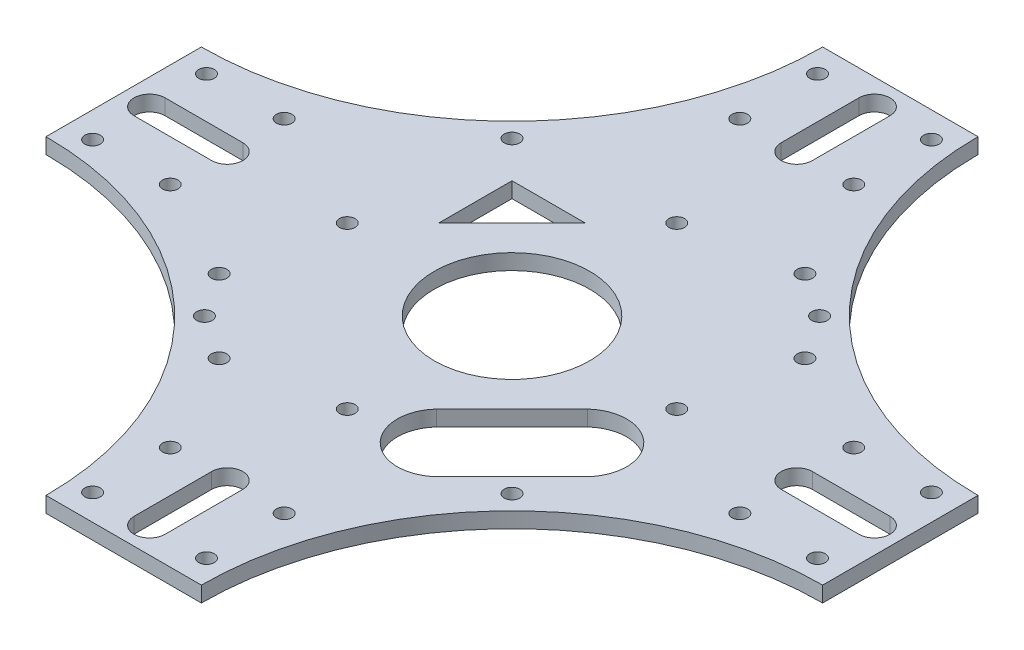
SolidWorks part; units mm, degrees
ref_plane "前视基准面" through (0, 0, 0) normal (0, 0, 1) x (1, 0, 0)
ref_plane "上视基准面" through (0, 0, 0) normal (0, 1, 0) x (1, 0, 0)
ref_plane "右视基准面" through (0, 0, 0) normal (1, 0, 0) x (0, 0, -1)
sketch "草图1" plane through (0, 0, 0) normal (0, 1, 0) x (1, 0, 0)
  line L0 (0, 0) -> (0, 75)
  line L1 (0, 0) -> (75, 0)
  line L2 (0, 0) -> (0, -75)
  line L3 (0, 0) -> (-75, 0)
  line L4 (0, 75) -> (15, 75)
  line L5 (0, 75) -> (-15, 75)
  line L6 (75, 0) -> (75, 15)
  line L7 (75, 0) -> (75, -15)
  line L8 (0, -75) -> (15, -75)
  line L9 (0, -75) -> (-15, -75)
  line L10 (-75, 0) -> (-75, -15)
  line L11 (-75, 0) -> (-75, 15)
  line L12 (75, 0) -> (70, 0)
  arc A0 (-75, 15) -> (-15, 75) centre (-75, 75) ccw
  arc A1 (15, 75) -> (75, 15) centre (75, 75) ccw
  arc A2 (75, -15) -> (15, -75) centre (75, -75) ccw
  arc A3 (-15, -75) -> (-75, -15) centre (-75, -75) ccw
  circle A4 centre (-11, 70) radius 1.25
  circle A5 centre (11, 70) radius 1.25
  circle A6 centre (70, -11) radius 1.25
  circle A7 centre (70, 11) radius 1.25
  circle A8 centre (-11, -70) radius 1.25
  circle A9 centre (11, -70) radius 1.25
  circle A10 centre (-70, 11) radius 1.25
  circle A11 centre (-70, -11) radius 1.25
  point P9 (0, 0)
  point P21 (0, 0)
  point P32 (0, 0)
  point P35 (0, 0)
  point P44 (0, 0)
  dimension "D1" = 4
extrude "凸台-拉伸1" add sketch "草图1" along normal blind 3 contours A2 L7 L1 L2 L8 A9 A6 | A3 L9 L2 L3 L10 A11 A8 | A0 L11 L3 L0 L5 A4 A10 | A1 L4 L0 L1 L6 A7 A5
sketch "草图2" plane through (0, 0, 0) normal (0, -1, 0) x (1, 0, 0)
  line L0 (0, 0) -> (-32.5736, -32.5736)
  line L1 (0, 0) -> (32.5736, -32.5736)
  line L2 (-31.4663, 0.3536) -> (-0.3536, 31.4663)
  line L3 (31.4663, -0.3536) -> (-0.3536, 31.4663)
  line L4 (0.3536, -31.4663) -> (31.4663, -0.3536)
  line L5 (0.3536, -31.4663) -> (-31.4663, 0.3536)
  arc A0 (-15, -75) -> (-75, -15) centre (-75, -75) ccw construction
  circle A2 centre (0.3536, -31.4663) radius 1.5
  circle A3 centre (31.4663, -0.3536) radius 1.5
  circle A4 centre (-0.3536, 31.4663) radius 1.5
  circle A5 centre (-31.4663, 0.3536) radius 1.5
  point P12 (-15.5563, -15.5563)
  point P16 (-15.9099, 15.9099)
  point P17 (15.9099, -15.9099)
extrude "切除-拉伸1" cut sketch "草图2" against normal blind 3 contours A3 | A2 | A5 | A4
sketch "草图3" plane through (0, 3, 0) normal (0, 1, 0) x (1, 0, 0)
  line L0 (0.3536, 31.4663) -> (-31.4663, -0.3536)
  line L1 (-15.5563, 15.5563) -> (-22.6274, 22.6274)
  line L2 (-15.5563, 15.5563) -> (-12.0208, 19.0919)
  line L3 (-15.5563, 15.5563) -> (-19.0919, 12.0208)
  line L4 (-19.0919, 12.0208) -> (-22.6274, 22.6274)
  line L5 (-12.0208, 19.0919) -> (-22.6274, 22.6274)
extrude "切除-拉伸2" cut sketch "草图3" against normal blind 3 contours L0 L5 L1 | L4 L0 L1
sketch "草图4" plane through (0, 3, 0) normal (0, 1, 0) x (1, 0, 0)
  line L0 (31.4663, 0.3536) -> (-0.3536, -31.4663)
  line L1 (0, 0) -> (21.2132, -21.2132)
  line L2 (28.2843, -14.1421) -> (14.1421, -28.2843)
  line L3 (14.1421, -28.2843) -> (28.2843, -14.1421) construction
  line L4 (8.4817, -22.6239) -> (22.6239, -8.4817)
  line L5 (19.8025, -33.9447) -> (33.9447, -19.8025)
  arc A0 (8.4817, -22.6239) -> (19.8025, -33.9447) centre (14.1421, -28.2843) ccw
  arc A1 (33.9447, -19.8025) -> (22.6239, -8.4817) centre (28.2843, -14.1421) ccw
  point P9 (21.2132, -21.2132)
extrude "切除-拉伸3" cut sketch "草图4" against normal blind 3
sketch "草图5" plane through (0, 3, 0) normal (0, 1, 0) x (1, 0, 0)
  line L0 (-12.0208, 19.0919) -> (-8.4853, 22.6274)
  line L1 (-8.4853, 22.6274) -> (-22.6274, 22.6274)
  line L2 (-19.0919, 12.0208) -> (-22.6274, 8.4853)
  line L3 (-22.6274, 8.4853) -> (-22.6274, 22.6274)
  line L4 (-12.0208, 19.0919) -> (-22.6274, 22.6274)
  line M28 (-19.0919, 12.0208) -> (-22.6274, 22.6274)
extrude "切除-拉伸4" cut sketch "草图5" against normal blind 10 contours L3 L2 M28 | L4 L0 L1
sketch "草图6" plane through (0, 3, 0) normal (0, 1, 0) x (1, 0, 0)
  line L0 (0, 0) -> (-28.2843, -28.2843)
  line L1 (-28.2843, -28.2843) -> (-35.3553, -21.2132)
  line L2 (0, 0) -> (-22.6274, 22.6274)
  circle A0 centre (-35.3553, -21.2132) radius 1.5
  circle A1 centre (-21.2132, -35.3553) radius 1.5
  circle A2 centre (35.3553, 21.2132) radius 1.5
  circle A3 centre (21.2132, 35.3553) radius 1.5
extrude "切除-拉伸5" cut sketch "草图6" against normal blind 10 contours A1 | A0 | A2 | A3
sketch "草图7" plane through (0, 3, 0) normal (0, 1, 0) x (1, 0, 0)
  circle A0 centre (-29.6985, 29.6985) radius 1.5
  circle A1 centre (29.6985, 29.6985) radius 1.5
  circle A2 centre (29.6985, -29.6985) radius 1.5
  circle A3 centre (-29.6985, -29.6985) radius 1.5
  point P11 (0, 0)
  dimension "D1" = 4
extrude "切除-拉伸8" cut sketch "草图7" against normal blind 10
sketch "草图8" plane through (0, 3, 0) normal (0, 1, 0) x (1, 0, 0)
  circle A0 centre (-11, 55) radius 1.5
  circle A1 centre (11, 55) radius 1.5
  circle A2 centre (55, 11) radius 1.5
  circle A3 centre (55, -11) radius 1.5
  circle A4 centre (11, -55) radius 1.5
  circle A5 centre (-11, -55) radius 1.5
  circle A6 centre (-55, -11) radius 1.5
  circle A7 centre (-55, 11) radius 1.5
  point P21 (0, 0)
  dimension "D1" = 4
extrude "切除-拉伸9" cut sketch "草图8" against normal blind 10
sketch "草图9" plane through (0, 3, 0) normal (0, 1, 0) x (1, 0, 0)
  circle A0 centre (0, 0) radius 15
extrude "切除-拉伸10" cut sketch "草图9" against normal blind 10
sketch "草图10" plane through (0, 3, 0) normal (0, 1, 0) x (1, 0, 0)
  circle A0 centre (11, 70) radius 1.5
  circle A1 centre (-11, 70) radius 1.5
  circle A2 centre (70, 11) radius 1.5
  circle A3 centre (70, -11) radius 1.5
  circle A4 centre (11, -70) radius 1.5
  circle A5 centre (-11, -70) radius 1.5
  circle A6 centre (-70, -11) radius 1.5
  circle A7 centre (-70, 11) radius 1.5
  point P21 (0, 0)
  dimension "D1" = 4
extrude "切除-拉伸11" cut sketch "草图10" against normal blind 10
sketch "草图11" plane through (0, 3, 0) normal (0, 1, 0) x (1, 0, 0)
  line L3 (0, 70) -> (0, 55)
  line L4 (0, 70) -> (0, 55) construction
  line L5 (3, 70) -> (3, 55)
  line L6 (-3, 70) -> (-3, 55)
  line L7 (70, 0) -> (55, 0) construction
  line L8 (70, -3) -> (55, -3)
  line L9 (70, 3) -> (55, 3)
  line L10 (0, -70) -> (0, -55) construction
  line L11 (-3, -70) -> (-3, -55)
  line L12 (3, -70) -> (3, -55)
  line L13 (-70, 0) -> (-55, 0) construction
  line L14 (-70, 3) -> (-55, 3)
  line L15 (-70, -3) -> (-55, -3)
  arc A0 (3, 70) -> (-3, 70) centre (0, 70) ccw
  arc A1 (-3, 55) -> (3, 55) centre (0, 55) ccw
  arc A2 (70, -3) -> (70, 3) centre (70, 0) ccw
  arc A3 (55, 3) -> (55, -3) centre (55, 0) ccw
  arc A4 (-3, -70) -> (3, -70) centre (0, -70) ccw
  arc A5 (3, -55) -> (-3, -55) centre (0, -55) ccw
  arc A6 (-70, 3) -> (-70, -3) centre (-70, 0) ccw
  arc A7 (-55, -3) -> (-55, 3) centre (-55, 0) ccw
  point P10 (0, 62.5)
  point P20 (62.5, 0)
  point P27 (0, -62.5)
  point P34 (-62.5, 0)
  point P39 (0, 0)
  dimension "D1" = 4
extrude "切除-拉伸12" cut sketch "草图11" against normal blind 10
